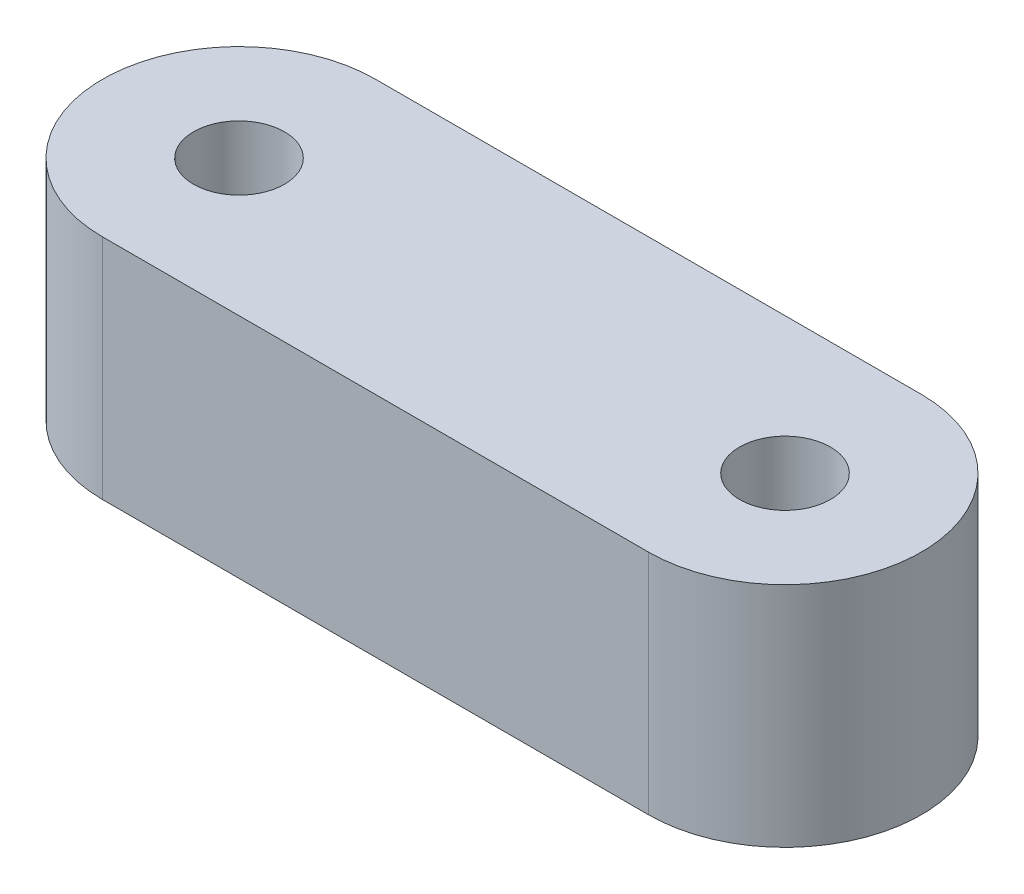
SolidWorks part; units mm, degrees
ref_plane "Front Plane" through (0, 0, 0) normal (0, 0, 1) x (1, 0, 0)
ref_plane "Top Plane" through (0, 0, 0) normal (0, 1, 0) x (1, 0, 0)
ref_plane "Right Plane" through (0, 0, 0) normal (1, 0, 0) x (0, 0, -1)
sketch "Sketch3" plane through (0, 0, 0) normal (0, 1, 0) x (1, 0, 0)
  line L0 (-50.8, 0) -> (-20.32, 0) construction
  line L1 (-6.985, 0) -> (6.985, 0) construction
  line L2 (-50.8, 7.62) -> (-20.32, 7.62)
  line L3 (-50.8, -7.62) -> (-20.32, -7.62)
  arc A0 (-50.8, 7.62) -> (-50.8, -7.62) centre (-50.8, 0) ccw
  arc A1 (-20.32, -7.62) -> (-20.32, 7.62) centre (-20.32, 0) ccw
  point P5 (-35.56, 0)
  dimension "D2" = 7.62
  dimension "D1" = 30.48
  dimension "D3" = 50.8
extrude "Boss-Extrude1" add sketch "Sketch3" along normal blind 12.7
sketch "Sketch4" plane through (0, 12.7, 0) normal (0, 1, 0) x (1, 0, 0)
  circle A0 centre (-50.8, 0) radius 2.54
  circle A1 centre (-20.32, 0) radius 2.54
  dimension "D1" = 5.08
extrude "Cut-Extrude3" cut sketch "Sketch4" against normal through all
equation "\"TibiaLength\"= 4in"
equation "\"TibiaRadius\"= 0.3in"
equation "\"TibiaDistFromCentre\"= \"TibiaLength\" / 2"
equation "\"TibiaThickness\"= 0.5in"
equation "\"HoleRadius\"= 0.2in"
equation "\"D1@Sketch3\"= \"TibiaLength\" * 0.3"
equation "\"D2@Sketch3\"= \"TibiaRadius\""
equation "\"D3@Sketch3\"= \"TibiaDistFromCentre\""
equation "\"D1@Boss-Extrude1\"= \"TibiaThickness\""
equation "\"D1@Sketch4\"= \"HoleRadius\""
